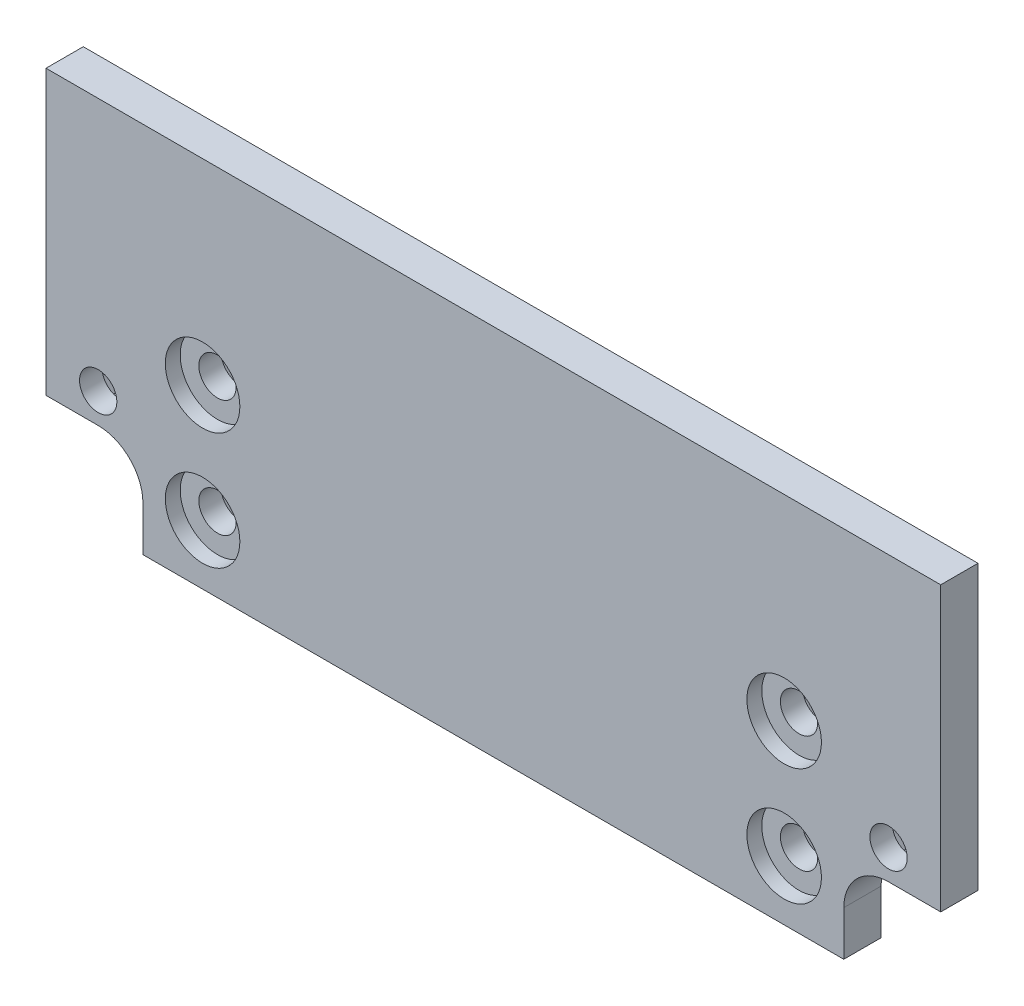
SolidWorks part; units mm, degrees
ref_plane "前视基准面" through (0, 0, 0) normal (0, 0, 1) x (1, 0, 0)
ref_plane "上视基准面" through (0, 0, 0) normal (0, 1, 0) x (1, 0, 0)
ref_plane "右视基准面" through (0, 0, 0) normal (1, 0, 0) x (0, 0, -1)
sketch "草图1" plane through (0, 0, 0) normal (0, 0, 1) x (1, 0, 0)
  line L1 (-60, 25) -> (60, 25)
  line L2 (-60, 25) -> (-60, -25)
  line L3 (-60, -25) -> (60, -25)
  line L4 (60, 25) -> (60, -25)
  line L5 (-60, 25) -> (60, -25) construction
  line L6 (-60, -25) -> (60, 25) construction
  circle A0 centre (-53, -9) radius 2.5
  circle A1 centre (53, -9) radius 2.5
  point P0 (0, 0)
  point P5 (0, 0)
  point P6 (0, 0)
  dimension "D5" = 5
  dimension "D6" = 5
  dimension "D1" = 50
  dimension "D2" = 120
  dimension "D3" = 16
  dimension "D4" = 16
  dimension "D7" = 53
  dimension "D8" = 53
sketch "草图4" plane through (0, 0, 0) normal (0, 0, 1) x (1, 0, 0)
  line L2 (-60, -25) -> (60, -25) construction
  line L3 (60, 25) -> (60, -25) construction
  circle A0 centre (-39, -1.3) radius 2.5
  circle A1 centre (-39, -17) radius 2.5
  circle A2 centre (39, -1.3) radius 2.5
  circle A3 centre (39, -17) radius 2.5
  point P0 (0, -9.15)
  dimension "D5" = 5
  dimension "D6" = 5
  dimension "D7" = 5
  dimension "D8" = 5
  dimension "D1" = 15.7
  dimension "D2" = 78
  dimension "D3" = 15.7
  dimension "D4" = 0
  dimension "D9" = 78
  dimension "D10" = 8
  dimension "D11" = 21
extrude "凸台-拉伸2" add sketch "草图1" along normal blind 5
extrude "切除-拉伸1" cut sketch "草图4" along normal through all
sketch "草图7" plane through (0, 0, 5) normal (0, 0, 1) x (1, 0, 0)
  circle A0 centre (-39, -1.3) radius 5
  circle A1 centre (-39, -17) radius 5
  circle A2 centre (39, -1.3) radius 5
  circle A3 centre (39, -17) radius 5
  dimension "D1" = 10
  dimension "D2" = 10
  dimension "D3" = 10
  dimension "D4" = 10
extrude "切除-拉伸4" cut sketch "草图7" against normal blind 2
sketch "草图9" plane through (0, 0, 0) normal (0, 0, -1) x (-1, 0, 0)
  line L1 (-34.0925, -1.3) -> (-36.5463, 2.95)
  line L2 (-36.5463, 2.95) -> (-41.4537, 2.95)
  line L3 (-41.4537, 2.95) -> (-43.9075, -1.3)
  line L4 (-43.9075, -1.3) -> (-41.4537, -5.55)
  line L5 (-41.4537, -5.55) -> (-36.5463, -5.55)
  line L6 (-36.5463, -5.55) -> (-34.0925, -1.3)
  line L7 (-34.0925, -17) -> (-36.5463, -12.75)
  line L8 (-36.5463, -12.75) -> (-41.4537, -12.75)
  line L9 (-41.4537, -12.75) -> (-43.9075, -17)
  line L10 (-43.9075, -17) -> (-41.4537, -21.25)
  line L11 (-41.4537, -21.25) -> (-36.5463, -21.25)
  line L12 (-36.5463, -21.25) -> (-34.0925, -17)
  line L13 (43.9075, -1.3) -> (41.4537, 2.95)
  line L14 (41.4537, 2.95) -> (36.5463, 2.95)
  line L15 (36.5463, 2.95) -> (34.0925, -1.3)
  line L16 (34.0925, -1.3) -> (36.5463, -5.55)
  line L17 (36.5463, -5.55) -> (41.4537, -5.55)
  line L18 (41.4537, -5.55) -> (43.9075, -1.3)
  line L19 (43.9075, -17) -> (41.4537, -12.75)
  line L20 (41.4537, -12.75) -> (36.5463, -12.75)
  line L21 (36.5463, -12.75) -> (34.0925, -17)
  line L22 (34.0925, -17) -> (36.5463, -21.25)
  line L23 (36.5463, -21.25) -> (41.4537, -21.25)
  line L24 (41.4537, -21.25) -> (43.9075, -17)
  line L25 (-35.2472, -1.3) -> (-37.1236, 1.95)
  line L26 (-37.1236, 1.95) -> (-40.8764, 1.95)
  line L27 (-40.8764, 1.95) -> (-42.7528, -1.3)
  line L28 (-42.7528, -1.3) -> (-40.8764, -4.55)
  line L29 (-40.8764, -4.55) -> (-37.1236, -4.55)
  line L30 (-37.1236, -4.55) -> (-35.2472, -1.3)
  line L31 (-35.2472, -17) -> (-37.1236, -13.75)
  line L32 (-37.1236, -13.75) -> (-40.8764, -13.75)
  line L33 (-40.8764, -13.75) -> (-42.7528, -17)
  line L34 (-42.7528, -17) -> (-40.8764, -20.25)
  line L35 (-40.8764, -20.25) -> (-37.1236, -20.25)
  line L36 (-37.1236, -20.25) -> (-35.2472, -17)
  line L37 (42.7528, -1.3) -> (40.8764, 1.95)
  line L38 (40.8764, 1.95) -> (37.1236, 1.95)
  line L39 (37.1236, 1.95) -> (35.2472, -1.3)
  line L40 (35.2472, -1.3) -> (37.1236, -4.55)
  line L41 (37.1236, -4.55) -> (40.8764, -4.55)
  line L42 (40.8764, -4.55) -> (42.7528, -1.3)
  line L43 (42.7528, -17) -> (40.8764, -13.75)
  line L44 (40.8764, -13.75) -> (37.1236, -13.75)
  line L45 (37.1236, -13.75) -> (35.2472, -17)
  line L46 (35.2472, -17) -> (37.1236, -20.25)
  line L47 (37.1236, -20.25) -> (40.8764, -20.25)
  line L48 (40.8764, -20.25) -> (42.7528, -17)
  circle A0 centre (-39, -1.3) radius 4.25 construction
  circle A1 centre (-39, -17) radius 4.25 construction
  circle A2 centre (39, -1.3) radius 4.25 construction
  circle A3 centre (39, -17) radius 4.25 construction
  circle A4 centre (-39, -1.3) radius 3.25 construction
  circle A5 centre (-39, -17) radius 3.25 construction
  circle A6 centre (39, -1.3) radius 3.25 construction
  circle A7 centre (39, -17) radius 3.25 construction
  dimension "D1" = 6.5
  dimension "D2" = 8.5
  dimension "D3" = 6.5
  dimension "D4" = 8.5
  dimension "D5" = 6.5
  dimension "D6" = 8.5
  dimension "D7" = 6.5
  dimension "D8" = 8.5
extrude "凸台-拉伸3" add sketch "草图9" along normal blind 5
sketch "草图11" plane through (60, 0, 0) normal (1, 0, 0) x (0, 0, -1)
  line L0 (0, -25) -> (0, 25) construction
  line L1 (-5, -25) -> (0, -25)
  line L2 (-5, -25) -> (-5, -13)
  line L3 (-5, -13) -> (0, -13)
  line L4 (0, -25) -> (0, -13)
  dimension "D1" = 12
extrude "切除-拉伸5" cut sketch "草图11" against normal blind 13
fillet "圆角3" radius 6 1 edges at (47, -13, 2.5)
sketch "草图12" plane through (-60, 0, 0) normal (-1, 0, 0) x (0, 0, 1)
  line L0 (5, 25) -> (5, -25) construction
  line L1 (0, -25) -> (5, -25)
  line L2 (0, -25) -> (0, -13)
  line L3 (0, -13) -> (5, -13)
  line L4 (5, -25) -> (5, -13)
  dimension "D1" = 12
extrude "切除-拉伸6" cut sketch "草图12" against normal blind 13
fillet "圆角4" radius 6 1 edges at (-47, -13, 2.5)
sketch "草图13" plane through (0, 0, 0) normal (0, 0, -1) x (-1, 0, 0)
  line L1 (-49.2472, -9) -> (-51.1236, -5.75)
  line L2 (-51.1236, -5.75) -> (-54.8764, -5.75)
  line L3 (-54.8764, -5.75) -> (-56.7528, -9)
  line L4 (-56.7528, -9) -> (-54.8764, -12.25)
  line L5 (-54.8764, -12.25) -> (-51.1236, -12.25)
  line L6 (-51.1236, -12.25) -> (-49.2472, -9)
  line L7 (56.7528, -9) -> (54.8764, -5.75)
  line L8 (54.8764, -5.75) -> (51.1236, -5.75)
  line L9 (51.1236, -5.75) -> (49.2472, -9)
  line L10 (49.2472, -9) -> (51.1236, -12.25)
  line L11 (51.1236, -12.25) -> (54.8764, -12.25)
  line L12 (54.8764, -12.25) -> (56.7528, -9)
  circle A0 centre (-53, -9) radius 3.25 construction
  circle A1 centre (53, -9) radius 3.25 construction
  dimension "D1" = 6.5
  dimension "D2" = 6.5
extrude "切除-拉伸7" cut sketch "草图13" against normal blind 2
